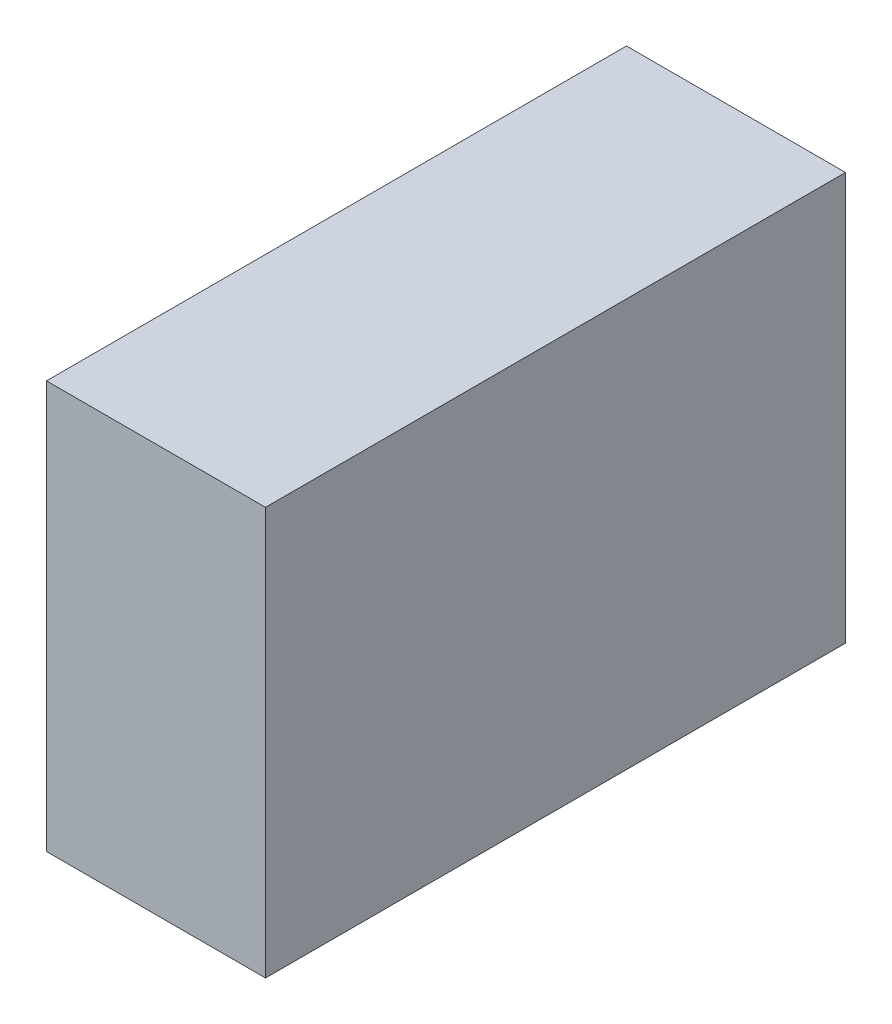
SolidWorks part; units mm, degrees
ref_plane "Front Plane" through (0, 0, 0) normal (0, 0, 1) x (1, 0, 0)
ref_plane "Top Plane" through (0, 0, 0) normal (0, 1, 0) x (1, 0, 0)
ref_plane "Right Plane" through (0, 0, 0) normal (1, 0, 0) x (0, 0, -1)
sketch "Sketch1" plane through (0, 0, 0) normal (0, 1, 0) x (1, 0, 0)
  line L1 (0, 0) -> (171.45, 0)
  line L2 (0, 0) -> (0, 454.025)
  line L3 (0, 454.025) -> (171.45, 454.025)
  line L4 (171.45, 0) -> (171.45, 454.025)
  dimension "D1" = 171.45
  dimension "D2" = 454.025
extrude "Boss-Extrude1" add sketch "Sketch1" along normal blind 319.0875
